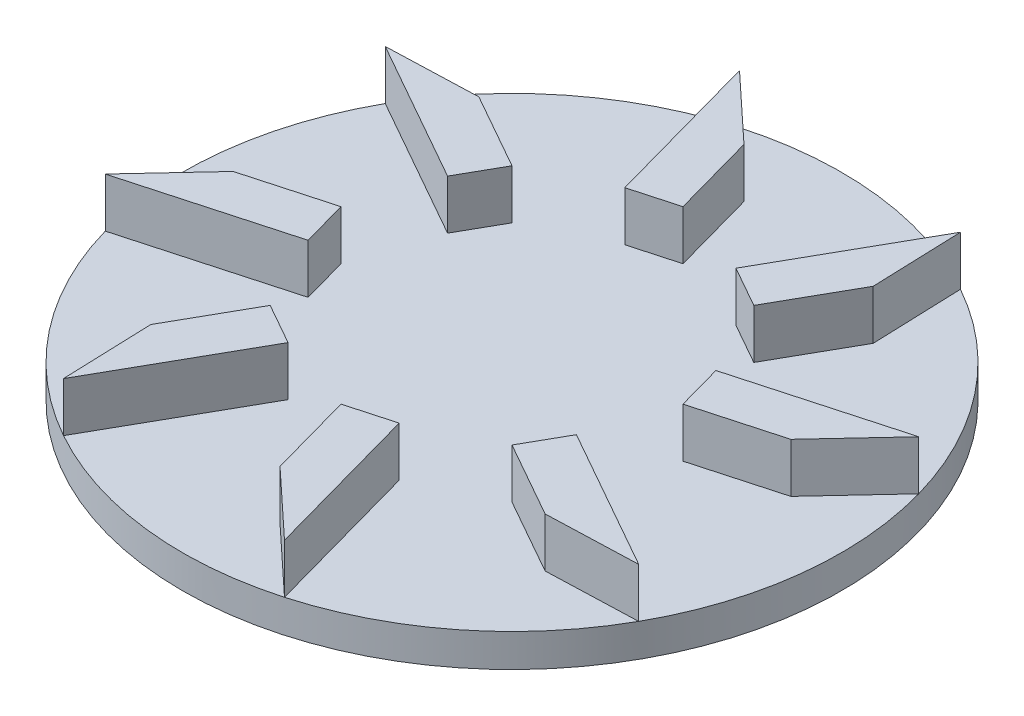
SolidWorks part; units mm, degrees
ref_plane "前视基准面" through (0, 0, 0) normal (0, 0, 1) x (1, 0, 0)
ref_plane "上视基准面" through (0, 0, 0) normal (0, 1, 0) x (1, 0, 0)
ref_plane "右视基准面" through (0, 0, 0) normal (1, 0, 0) x (0, 0, -1)
other "Configuration Table"
sketch "草图1" plane through (0, 0, 0) normal (0, 1, 0) x (1, 0, 0)
  circle A0 centre (0, 0) radius 20
extrude "凸台-拉伸1" add sketch "草图1" along normal blind 2
sketch "草图2" plane through (0, 2, 0) normal (0, 1, 0) x (1, 0, 0)
  line L0 (0, -23.0354) -> (0, 29.5369) construction
  line L1 (1.422, -15.5013) -> (0, -10.3778)
  line L2 (0, -10.3778) -> (2.7643, -9.6106)
  line L3 (2.7643, -9.6106) -> (5.4387, -19.2463)
  line L4 (5.4387, -19.2463) -> (1.422, -15.5013)
  line L5 (-9.9556, -11.9666) -> (-7.3382, -7.3382)
  line L6 (-7.3382, -7.3382) -> (-4.841, -8.7504)
  line L7 (-4.841, -8.7504) -> (-9.7634, -17.4549)
  line L8 (-9.7634, -17.4549) -> (-9.9556, -11.9666)
  line L9 (-15.5013, -1.422) -> (-10.3778, 0)
  line L10 (-10.3778, 0) -> (-9.6106, -2.7643)
  line L11 (-9.6106, -2.7643) -> (-19.2463, -5.4387)
  line L12 (-19.2463, -5.4387) -> (-15.5013, -1.422)
  line L13 (-11.9666, 9.9556) -> (-7.3382, 7.3382)
  line L14 (-7.3382, 7.3382) -> (-8.7504, 4.841)
  line L15 (-8.7504, 4.841) -> (-17.4549, 9.7634)
  line L16 (-17.4549, 9.7634) -> (-11.9666, 9.9556)
  line L17 (-1.422, 15.5013) -> (0, 10.3778)
  line L18 (0, 10.3778) -> (-2.7643, 9.6106)
  line L19 (-2.7643, 9.6106) -> (-5.4387, 19.2463)
  line L20 (-5.4387, 19.2463) -> (-1.422, 15.5013)
  line L21 (9.9556, 11.9666) -> (7.3382, 7.3382)
  line L22 (7.3382, 7.3382) -> (4.841, 8.7504)
  line L23 (4.841, 8.7504) -> (9.7634, 17.4549)
  line L24 (9.7634, 17.4549) -> (9.9556, 11.9666)
  line L25 (15.5013, 1.422) -> (10.3778, 0)
  line L26 (10.3778, 0) -> (9.6106, 2.7643)
  line L27 (9.6106, 2.7643) -> (19.2463, 5.4387)
  line L28 (19.2463, 5.4387) -> (15.5013, 1.422)
  line L29 (11.9666, -9.9556) -> (7.3382, -7.3382)
  line L30 (7.3382, -7.3382) -> (8.7504, -4.841)
  line L31 (8.7504, -4.841) -> (17.4549, -9.7634)
  line L32 (17.4549, -9.7634) -> (11.9666, -9.9556)
  circle A0 centre (0, 0) radius 20 construction
  point P11 (5.3497, -19.2712)
  point P12 (1.4607, -15.7875)
  point P40 (0, 0)
  point P41 (5.4387, -19.2463)
  dimension "D1" = 8
extrude "凸台-拉伸2" add sketch "草图2" along normal blind 3
